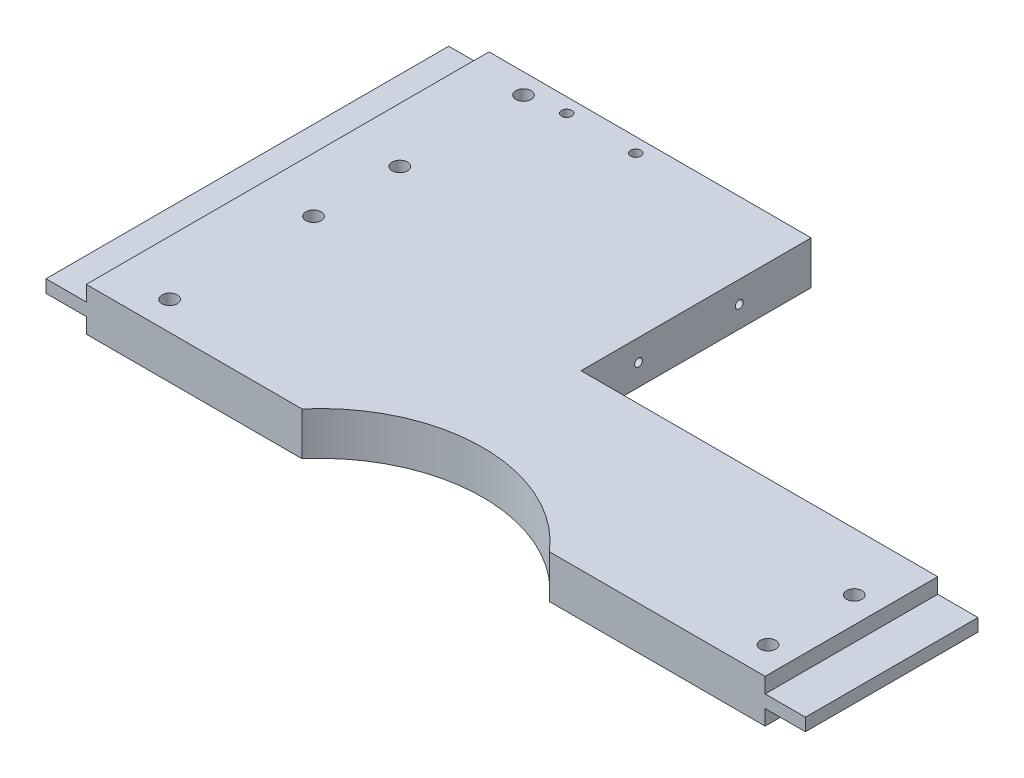
SolidWorks part; units mm, degrees
ref_plane "Front" through (0, 0, 0) normal (0, 0, 1) x (1, 0, 0)
ref_plane "Top" through (0, 0, 0) normal (0, 1, 0) x (1, 0, 0)
ref_plane "Right" through (0, 0, 0) normal (1, 0, 0) x (0, 0, -1)
sketch "Sketch1" plane through (0, 0, 0) normal (0, 1, 0) x (1, 0, 0)
  line L0 (-142.24, 101.6) -> (-142.24, -76.2)
  line L1 (-142.24, -76.2) -> (-46.99, -76.2)
  line L2 (-142.24, 101.6) -> (0, 101.6)
  line L3 (0, 101.6) -> (0, 0)
  line L4 (0, 0) -> (157.48, 0)
  line L5 (157.48, 0) -> (157.48, -76.2)
  line L6 (157.48, -76.2) -> (62.23, -76.2)
  circle A0 centre (7.62, -122.8202) radius 71.8032
  point P10 (0, 0)
  dimension "D1" = 76.2
  dimension "D2" = 95.25
  dimension "D3" = 95.25
  dimension "D4" = 142.24
  dimension "D5" = 101.6
  dimension "D6" = 299.72
extrude "Boss-Extrude1" add sketch "Sketch1" along normal mid plane 19.05 contours A0 L6 L5 L4 L3 L2 L0 L1
sketch "Sketch2" plane through (0, 0, 0) normal (0, 1, 0) x (1, 0, 0)
  line L0 (-142.24, -76.2) -> (-46.99, -76.2) construction
  line L1 (-142.24, 101.6) -> (-160.02, 101.6)
  line L2 (-142.24, 101.6) -> (-142.24, -76.2)
  line L3 (-142.24, -76.2) -> (-160.02, -76.2)
  line L4 (-160.02, 101.6) -> (-160.02, -76.2)
  line L5 (157.48, 0) -> (175.26, 0)
  line L6 (157.48, 0) -> (157.48, -76.2)
  line L7 (157.48, -76.2) -> (175.26, -76.2)
  line L8 (175.26, 0) -> (175.26, -76.2)
  line L9 (157.48, -76.2) -> (62.23, -76.2) construction
  dimension "D1" = 17.78
  dimension "D2" = 17.78
extrude "Boss-Extrude2" add sketch "Sketch2" along normal mid plane 5.588
sketch "Sketch3" plane through (0, 9.525, 0) normal (0, 1, 0) x (1, 0, 0)
  line L0 (-118.11, 101.6) -> (-118.11, -76.2) construction
  line L1 (-142.24, 101.6) -> (0, 101.6) construction
  line L2 (-142.24, -76.2) -> (-46.99, -76.2) construction
  line L3 (-142.24, -76.2) -> (-142.24, 101.6) construction
  line L4 (-142.24, 101.6) -> (-142.24, -76.2) construction
  line L5 (-142.24, 95.25) -> (0, 95.25) construction
  line L6 (0, 101.6) -> (0, 0) construction
  line L7 (146.05, 0) -> (146.05, -76.2) construction
  line L8 (0, 0) -> (157.48, 0) construction
  line L9 (157.48, -76.2) -> (62.23, -76.2) construction
  line L10 (157.48, 0) -> (157.48, -76.2) construction
  point P8 (-101.6, 95.25)
  point P9 (-71.12, 95.25)
  point P16 (-118.11, 0)
  point P17 (-118.11, 38.1)
  point P18 (-118.11, -63.5)
  point P19 (-118.11, 92.71)
  point P28 (146.05, -25.4)
  point P29 (146.05, -63.5)
  dimension "D1" = 24.13
  dimension "D2" = 40.64
  dimension "D3" = 71.12
  dimension "D4" = 8.89
  dimension "D5" = 12.7
  dimension "D6" = 76.2
  dimension "D7" = 114.3
  dimension "D8" = 6.35
  dimension "D9" = 11.43
  dimension "D10" = 12.7
  dimension "D11" = 25.4
hole_wizard "1/4 Clearance Hole1" positions "Sketch4" profile "Sketch6" hole size "1/4" standard "ANSI Inch" end condition through all
sketch "Sketch4" plane through (0, 9.525, 0) normal (0, 1, 0) x (1, 0, 0)
  point P0 (-118.11, 92.71)
  point P3 (-118.11, 38.1)
  point P6 (-118.11, 0)
  point P9 (-118.11, -63.5)
sketch "Sketch6" plane through (-118.11, 9.525, -92.71) normal (1, 0, 0) x (0, 0, 1)
  line L0 (0, 0) -> (0, 19.05)
  line L1 (0, 19.05) -> (3.3782, 19.05)
  line L2 (3.3782, 19.05) -> (3.3782, 0)
  line L5 (3.3782, 0) -> (0, 0)
  line L11 (0, -6.35) -> (0, 107.95) construction
  dimension "Thru Hole Dia." = 6.7564
  dimension "Thru Hole Depth" = 19.05
hole_wizard "#8 Clearance Hole1" positions "Sketch9" profile "Sketch10" hole size "#8" standard "ANSI Inch" end condition through all
sketch "Sketch9" plane through (0, 9.525, 0) normal (0, 1, 0) x (1, 0, 0)
  point P0 (-101.6, 95.25)
  point P3 (-71.12, 95.25)
sketch "Sketch10" plane through (-101.6, 9.525, -95.25) normal (1, 0, 0) x (0, 0, 1)
  line L0 (0, 0) -> (0, 19.05)
  line L1 (0, 19.05) -> (2.2479, 19.05)
  line L2 (2.2479, 19.05) -> (2.2479, 0)
  line L5 (2.2479, 0) -> (0, 0)
  line L11 (0, -6.35) -> (0, 107.95) construction
  dimension "Thru Hole Dia." = 4.4958
  dimension "Thru Hole Depth" = 19.05
hole_wizard "1/4 Clearance Hole2" positions "Sketch11" profile "Sketch12" hole size "1/4" standard "ANSI Inch" end condition through all
sketch "Sketch11" plane through (0, 9.525, 0) normal (0, 1, 0) x (1, 0, 0)
  point P0 (146.05, -25.4)
  point P3 (146.05, -63.5)
sketch "Sketch12" plane through (146.05, 9.525, 25.4) normal (1, 0, 0) x (0, 0, 1)
  line L0 (0, 0) -> (0, 19.05)
  line L1 (0, 19.05) -> (3.3782, 19.05)
  line L2 (3.3782, 19.05) -> (3.3782, 0)
  line L5 (3.3782, 0) -> (0, 0)
  line L11 (0, -6.35) -> (0, 107.95) construction
  dimension "Thru Hole Dia." = 6.7564
  dimension "Thru Hole Depth" = 19.05
sketch "Sketch13" plane through (0, 0, 0) normal (0, 0, -1) x (-1, 0, 0)
  line L0 (50, 0) -> (-50, 0) construction
  line L1 (-157.48, 9.525) -> (-157.48, 2.794) construction
  line L2 (0, 0) -> (-175.26, 0) construction
  line L3 (-175.26, 2.794) -> (-175.26, -2.794) construction
  point P0 (-137.16, 0)
  point P1 (-106.68, 0)
  point P2 (-55.88, 0)
  point P3 (-15.24, 0)
  point P13 (0, 0)
  point P14 (0, 0)
  point P15 (0, 0)
  point P16 (0, 0)
  dimension "D1" = 20.32
  dimension "D2" = 50.8
  dimension "D3" = 101.6
  dimension "D4" = 142.24
hole_wizard "#8-32 Tapped Hole1" positions "Sketch16" profile "Sketch18" tap size "#8-32" standard "ANSI Inch"
sketch "Sketch16" plane through (0, 0, 0) normal (0, 0, -1) x (-1, 0, 0)
  point P0 (-137.16, 0)
  point P3 (-106.68, 0)
  point P6 (-55.88, 0)
  point P9 (-15.24, 0)
sketch "Sketch18" plane through (137.16, 0, 0) normal (1, 0, 0) x (0, 1, 0)
  line L0 (0, 0) -> (0, 11.7058)
  line L1 (0, 11.7058) -> (1.7272, 10.668)
  line L2 (1.7272, 10.668) -> (1.7272, 0)
  line L5 (1.7272, 0) -> (0, 0)
  line L10 (0, 11.7058) -> (-1.7272, 10.668) construction
  line L11 (0, -6.35) -> (0, 107.95) construction
  dimension "Tap Drill Dia." = 3.4544
  dimension "Tap Drill Depth" = 10.668
  dimension "Drill Angle" = 118
cosmetic thread "Hole Thread1" parameters "D1"=8.382, "D2"=4.1656
cosmetic thread "Hole Thread2" parameters "D1"=8.382, "D2"=4.1656
cosmetic thread "Hole Thread3" parameters "D1"=8.382, "D2"=4.1656
cosmetic thread "Hole Thread4" parameters "D1"=8.382, "D2"=4.1656
sketch "Sketch19" plane through (0, 0, 0) normal (1, 0, 0) x (0, 0, -1)
  line L0 (0, 0) -> (101.6, 0) construction
  line L1 (101.6, 9.525) -> (101.6, -9.525) construction
  point P5 (69.85, 0)
  point P6 (25.4, 0)
  dimension "D1" = 31.75
  dimension "D2" = 76.2
hole_wizard "#8-32 Tapped Hole2" positions "Sketch21" profile "Sketch22" tap size "#8-32" standard "ANSI Inch"
sketch "Sketch21" plane through (0, 0, 0) normal (1, 0, 0) x (0, 0, -1)
  point P0 (69.85, 0)
  point P3 (25.4, 0)
sketch "Sketch22" plane through (0, 0, -69.85) normal (0, 1, 0) x (0, 0, -1)
  line L0 (0, 0) -> (0, 11.7058)
  line L1 (0, 11.7058) -> (1.7272, 10.668)
  line L2 (1.7272, 10.668) -> (1.7272, 0)
  line L5 (1.7272, 0) -> (0, 0)
  line L10 (0, 11.7058) -> (-1.7272, 10.668) construction
  line L11 (0, -6.35) -> (0, 107.95) construction
  dimension "Tap Drill Dia." = 3.4544
  dimension "Tap Drill Depth" = 10.668
  dimension "Drill Angle" = 118
cosmetic thread "Hole Thread5" parameters "D1"=8.382, "D2"=4.1656
cosmetic thread "Hole Thread6" parameters "D1"=8.382, "D2"=4.1656
